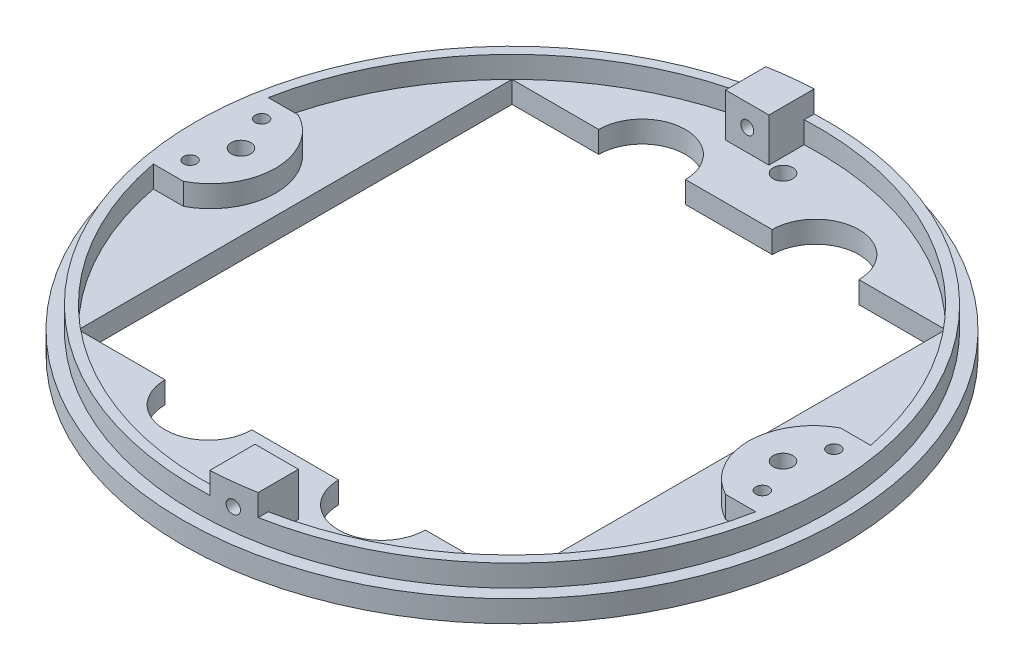
SolidWorks part; units mm, degrees
material "Custom Plastic"
ref_plane "Front Plane" through (0, 0, 0) normal (0, 0, 1) x (1, 0, 0)
ref_plane "Top Plane" through (0, 0, 0) normal (0, 1, 0) x (1, 0, 0)
ref_plane "Right Plane" through (0, 0, 0) normal (1, 0, 0) x (0, 0, -1)
sketch "Sketch1" plane through (0, 0, 0) normal (0, 1, 0) x (1, 0, 0)
  line L0 (0, 0) -> (0, -17.9724) construction
  line L1 (-50, -50) -> (50, -50)
  line L2 (-50, -50) -> (-50, 50)
  line L3 (-50, 50) -> (50, 50)
  line L4 (50, -50) -> (50, 50)
  line L5 (-50, -50) -> (50, 50) construction
  line L6 (-50, 50) -> (50, -50) construction
  line L7 (0, 0) -> (14.9739, 0) construction
  line L8 (0, 62.5) -> (14.3316, 62.5) construction
  line L9 (0, 76) -> (25.822, 76) construction
  circle A0 centre (0, 0) radius 76
  circle A1 centre (0, 0) radius 62.5 construction
  circle A2 centre (0, 62.5) radius 5
  circle A3 centre (62.5, 0) radius 5
  circle A4 centre (0, -62.5) radius 5
  circle A5 centre (-62.5, 0) radius 5
  dimension "D1" = 152
  dimension "D4" = 125
  dimension "D5" = 10
  dimension "D2" = 100
  dimension "D3" = 100
extrude "Boss-Extrude1" add sketch "Sketch1" along normal blind 5 contours A0 | L2 L1 L4 L3
sketch "Sketch2" plane through (0, 5, 0) normal (0, 1, 0) x (1, 0, 0)
  circle A0 centre (0, 0) radius 62.5 construction
  circle A1 centre (-62.5, 0) radius 2.25
  circle A2 centre (0, 62.5) radius 2.25
  circle A3 centre (62.5, 0) radius 2.25
  circle A4 centre (0, -62.5) radius 2.25
  dimension "D1" = 125
  dimension "D3" = 4.5
extrude "Cut-Extrude1" cut sketch "Sketch2" against normal blind 10
sketch "Sketch5" plane through (0, 5, 0) normal (0, 1, 0) x (1, 0, 0)
  circle A0 centre (0, 0) radius 76 construction
  circle A1 centre (0, 0) radius 76
  circle A2 centre (0, 0) radius 73
  circle A3 centre (0, 0) radius 70.7107
  dimension "D1" = 3
extrude "Boss-Extrude3" add sketch "Sketch5" along normal blind 5 contours A2 | A3
sketch "Sketch10" plane through (0, 5, 0) normal (0, 1, 0) x (1, 0, 0)
  line L0 (2.25, 62.5) -> (-2.25, 62.5)
  line L1 (-2.25, 62.5) -> (-3.25, 62.5)
  line L2 (-3.25, 62.5) -> (-13.25, 62.5)
  line L3 (-3.25, 62.5) -> (-3.25, 72.9276)
  line L4 (-13.25, 62.5) -> (-13.25, 71.7874)
  line L5 (-2.25, -62.5) -> (2.25, -62.5)
  line L6 (2.25, -62.5) -> (3.25, -62.5)
  line L7 (3.25, -62.5) -> (13.25, -62.5)
  line L8 (13.25, -62.5) -> (13.25, -71.7874)
  line L9 (3.25, -62.5) -> (3.25, -72.9276)
  circle A0 centre (0, 62.5) radius 2.25 construction
  circle A1 centre (0, 0) radius 73 construction
  circle A2 centre (0, 0) radius 73
  circle A3 centre (0, -62.5) radius 2.25 construction
  arc M8 (50, 50) -> (-50, 50) centre (0, 0) ccw
  dimension "D1" = 1
  dimension "D2" = 10
  dimension "D3" = 1
  dimension "D4" = 10
extrude "Boss-Extrude6" add sketch "Sketch10" along normal blind 10 contours L9 A2 L8 L7 | L4 L2 L3 M8 | L3 A2 L4 M8
sketch "Sketch11" plane through (0, 0, -62.5) normal (0, 0, 1) x (1, 0, 0)
  line L0 (-8.25, 15) -> (-8.25, 5)
  line L1 (-3.25, 15) -> (-13.25, 15) construction
  line L2 (-3.25, 5) -> (-13.25, 5) construction
  circle A0 centre (-8.25, 10) radius 1.5
  dimension "D1" = 3
extrude "Cut-Extrude4" cut sketch "Sketch11" against normal blind 30 contours L0 A0 | L0 A0
sketch "Sketch12" plane through (0, 0, 62.5) normal (0, 0, -1) x (-1, 0, 0)
  line L0 (-8.25, 15) -> (-8.25, 5)
  line L1 (-3.25, 15) -> (-13.25, 15) construction
  line L2 (-3.25, 5) -> (-13.25, 5) construction
  circle A0 centre (-8.25, 10) radius 1.5
  dimension "D1" = 3
extrude "Cut-Extrude5" cut sketch "Sketch12" against normal blind 70 contours L0 A0 | L0 A0
sketch "Sketch13" plane through (0, 5, 0) normal (0, 1, 0) x (1, 0, 0)
  line L0 (-62.5, -2.25) -> (-62.5, 2.25)
  line L1 (-62.5, 2.25) -> (-62.5, 3.25)
  line L2 (-62.5, 3.25) -> (-62.5, 13.25)
  line L3 (-62.5, -2.25) -> (-62.5, -3.25)
  line L4 (-62.5, -3.25) -> (-62.5, -13.25)
  line L5 (-62.5, -13.25) -> (-71.7874, -13.25)
  line L6 (-62.5, -3.25) -> (-72.9276, -3.25)
  line L7 (-62.5, 3.25) -> (-72.9276, 3.25)
  line L8 (-62.5, 13.25) -> (-71.7874, 13.25)
  line L9 (0, 0) -> (0, 18.7492) construction
  line L10 (62.5, 13.25) -> (71.7874, 13.25)
  line L11 (62.5, 3.25) -> (72.9276, 3.25)
  line L12 (62.5, 3.25) -> (62.5, 13.25)
  line L13 (62.5, 2.25) -> (62.5, 3.25)
  line L14 (62.5, -2.25) -> (62.5, 2.25)
  line L15 (62.5, -2.25) -> (62.5, -3.25)
  line L16 (62.5, -3.25) -> (62.5, -13.25)
  line L17 (62.5, -13.25) -> (71.7874, -13.25)
  line L18 (62.5, -3.25) -> (72.9276, -3.25)
  line L19 (-62.5, 13.25) -> (-62.5, 2.25)
  circle A0 centre (-62.5, 0) radius 2.25 construction
  circle A1 centre (0, 0) radius 73 construction
  arc A2 (-71.7874, 13.25) -> (-71.7874, -13.25) centre (0, 0) ccw
  arc A3 (62.5, 13.25) -> (62.5, -13.25) centre (70.5, 0) ccw
  arc A4 (-62.5, 13.25) -> (-62.5, -13.25) centre (-70.5, 0) cw
  circle A6 centre (-62.5, 0) radius 2.25
  arc A7 (71.7874, -13.25) -> (71.7874, 13.25) centre (0, 0) ccw
  arc M14 (-50, 50) -> (-50, -50) centre (0, 0) ccw
  dimension "D3" = 8
  dimension "D1" = 1
  dimension "D2" = 10
extrude "Boss-Extrude7" add sketch "Sketch13" along normal blind 5 contours L11 A2 L10 L12 | L17 A2 L18 L16 | L4 L6 L5 M14 | L2 L8 L7 M14 | L8 A2 L7 M14 | L6 A2 L5 M14
sketch "Sketch14" plane through (0, 10, 0) normal (0, 1, 0) x (1, 0, 0)
  line L0 (-65.9791, 13.25) -> (-65.9791, 3.25)
  line L1 (-62.5, 13.25) -> (-69.4582, 13.25) construction
  line L2 (-62.5, 3.25) -> (-70.636, 3.25) construction
  line L3 (-65.9791, -13.25) -> (-65.9791, -3.25)
  line L4 (-62.5, -13.25) -> (-69.4582, -13.25) construction
  line L5 (-62.5, -3.25) -> (-70.636, -3.25) construction
  line L6 (0, 0) -> (0, 25.5335) construction
  line L7 (65.9791, -13.25) -> (65.9791, -3.25)
  line L8 (65.9791, 13.25) -> (65.9791, 3.25)
  circle A0 centre (-65.9791, -8.25) radius 1.5
  circle A1 centre (-65.9791, 8.25) radius 1.5
  circle A2 centre (65.9791, -8.25) radius 1.5
  circle A3 centre (65.9791, 8.25) radius 1.5
  dimension "D1" = 3
  dimension "D2" = 3
extrude "Cut-Extrude6" cut sketch "Sketch14" against normal blind 44 contours L0 A1 | L0 A1 | L3 A0 | L3 A0 | A3 | A2
sketch "Sketch16" plane through (0, 5, 0) normal (0, 1, 0) x (1, 0, 0)
  line L0 (0, -50) -> (10, -50)
  line L1 (-50, -50) -> (50, -50) construction
  line L2 (0, 0) -> (-29.5123, 0) construction
  line L3 (0, 0) -> (0, 23.7209) construction
  line L4 (-30, 50) -> (-10, 50)
  line L5 (10, 50) -> (30, 50)
  line L6 (-30, -50) -> (-10, -50)
  line L7 (10, -50) -> (30, -50)
  arc A0 (10, -50) -> (30, -50) centre (20, -50) ccw
  arc A1 (10, 50) -> (30, 50) centre (20, 50) cw
  arc A2 (-10, -50) -> (-30, -50) centre (-20, -50) cw
  arc A3 (-10, 50) -> (-30, 50) centre (-20, 50) ccw
  line M9 (50, -50) -> (-50, -50)
  dimension "D2" = 10
  dimension "D1" = 20
extrude "Cut-Extrude7" cut sketch "Sketch16" against normal blind 30 contours A2 M9 | A0 M9 | L4 A3 | A1 L5
sketch "Sketch17" plane through (0, 5, 0) normal (0, 1, 0) x (1, 0, 0)
  line L0 (-62.5, -3.25) -> (-62.5, -13.25) construction
  line L1 (-62.5, -3.25) -> (-70.636, -3.25) construction
  line L2 (-62.5, 3.25) -> (-70.636, 3.25) construction
  line L3 (-62.5, 3.25) -> (-62.5, 13.25) construction
  line L4 (-62.5, -3.25) -> (-62.5, -13.25)
  line L5 (-62.5, -3.25) -> (-70.636, -3.25)
  line L6 (-62.5, 3.25) -> (-70.636, 3.25)
  line L7 (-62.5, 3.25) -> (-62.5, 13.25)
  line L8 (0, 0) -> (0, -23.4543) construction
  line L9 (62.5, -3.25) -> (62.5, -13.25)
  line L10 (62.5, -3.25) -> (70.636, -3.25)
  line L11 (62.5, 3.25) -> (70.636, 3.25)
  line L12 (62.5, 3.25) -> (62.5, 13.25)
  circle A0 centre (-62.5, 0) radius 2.25 construction
  circle A1 centre (-62.5, 0) radius 2.25
  arc A2 (-62.5, -13.25) -> (-62.5, 13.25) centre (-69.5, 0) ccw
  arc A3 (-70.636, 3.25) -> (-70.636, -3.25) centre (0, 0) ccw construction
  arc A4 (-70.636, 3.25) -> (-70.636, -3.25) centre (0, 0) ccw
  arc A5 (62.5, -13.25) -> (62.5, 13.25) centre (69.5, 0) cw
  arc A6 (70.636, 3.25) -> (70.636, -3.25) centre (0, 0) cw
  circle A7 centre (62.5, 0) radius 2.25 construction
  circle A8 centre (62.5, 0) radius 2.25
  dimension "D1" = 7
extrude "Boss-Extrude9" add sketch "Sketch17" along normal blind 5
sketch "Sketch18" plane through (0, 0, 0) normal (0, -1, 0) x (1, 0, 0)
  circle A0 centre (0, -62.5) radius 2.25 construction
  circle A1 centre (0, 0) radius 76
  circle A2 centre (0, 0) radius 76
  circle A3 centre (-65.9791, -8.25) radius 1.5 construction
  circle A4 centre (-62.5, 0) radius 2.25 construction
  circle A5 centre (-65.9791, 8.25) radius 1.5 construction
  circle A6 centre (0, 62.5) radius 2.25 construction
  circle A7 centre (65.9791, 8.25) radius 1.5 construction
  circle A8 centre (65.9791, -8.25) radius 1.5 construction
  circle A9 centre (62.5, 0) radius 2.25 construction
  circle A10 centre (0, -62.5) radius 2.25
  circle A11 centre (-65.9791, -8.25) radius 1.5
  circle A12 centre (-62.5, 0) radius 2.25
  circle A13 centre (-65.9791, 8.25) radius 1.5
  circle A14 centre (0, 62.5) radius 2.25
  circle A15 centre (65.9791, 8.25) radius 1.5
  circle A16 centre (65.9791, -8.25) radius 1.5
  circle A17 centre (62.5, 0) radius 2.25
  dimension "D1" = 0
